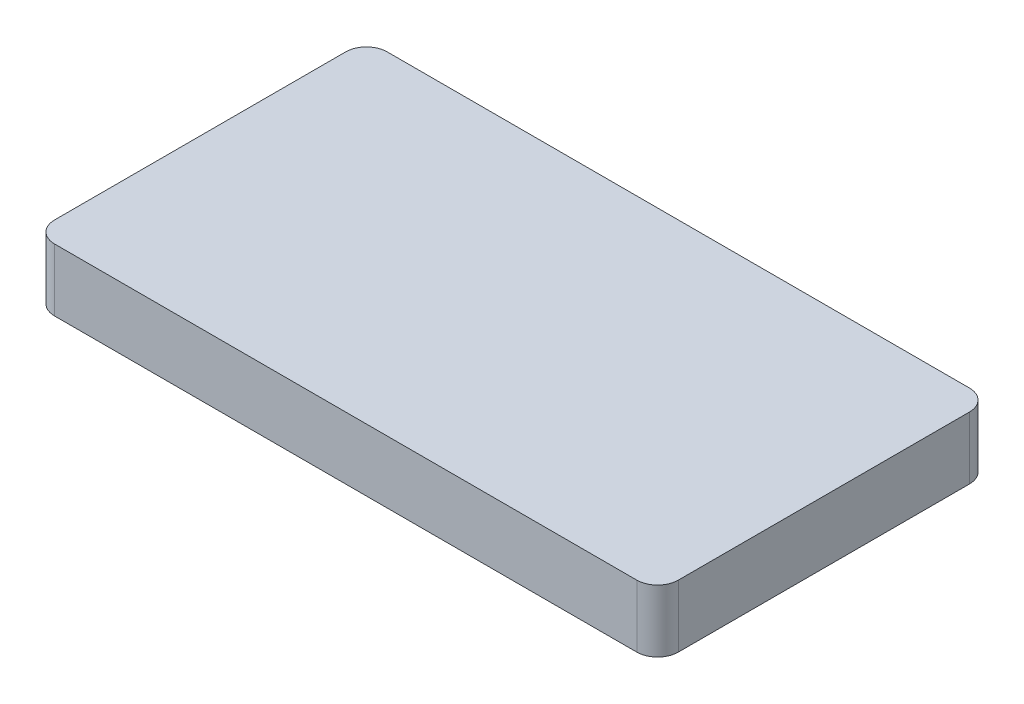
SolidWorks part; units mm, degrees
ref_plane "Front Plane" through (0, 0, 0) normal (0, 0, 1) x (1, 0, 0)
ref_plane "Top Plane" through (0, 0, 0) normal (0, 1, 0) x (1, 0, 0)
ref_plane "Right Plane" through (0, 0, 0) normal (1, 0, 0) x (0, 0, -1)
sketch "Sketch1" plane through (0, 0, 0) normal (0, 1, 0) x (1, 0, 0)
  line L1 (-75, -40) -> (75, -40)
  line L2 (-75, -40) -> (-75, 40)
  line L3 (-75, 40) -> (75, 40)
  line L4 (75, -40) -> (75, 40)
  line L5 (-75, -40) -> (75, 40) construction
  line L6 (-75, 40) -> (75, -40) construction
  point P0 (0, 0)
  dimension "D1" = 150
  dimension "D2" = 80
extrude "Boss-Extrude1" add sketch "Sketch1" along normal mid plane 15
sketch "Sketch2" plane through (0, 7.5, 0) normal (0, 1, 0) x (1, 0, 0)
  line L0 (-75, 0) -> (75, 0) construction
  line L1 (-75, 40) -> (-75, -40) construction
  line L2 (75, -40) -> (75, 40) construction
  line L4 (0, 40) -> (0, -40) construction
  line L5 (75, 40) -> (-75, 40) construction
  line L6 (-75, -40) -> (75, -40) construction
sketch "Sketch5" plane through (0, 7.5, 0) normal (0, 1, 0) x (1, 0, 0)
  line L0 (-75, 0) -> (75, 0) construction
  point P0 (-30, 0)
  point P1 (30, 0)
  dimension "D1" = 30
  dimension "D2" = 30
fillet "Fillet1" radius 5 4 edges at (75, 0, 40) (75, 0, -40) (-75, 0, 40) (-75, 0, -40)
